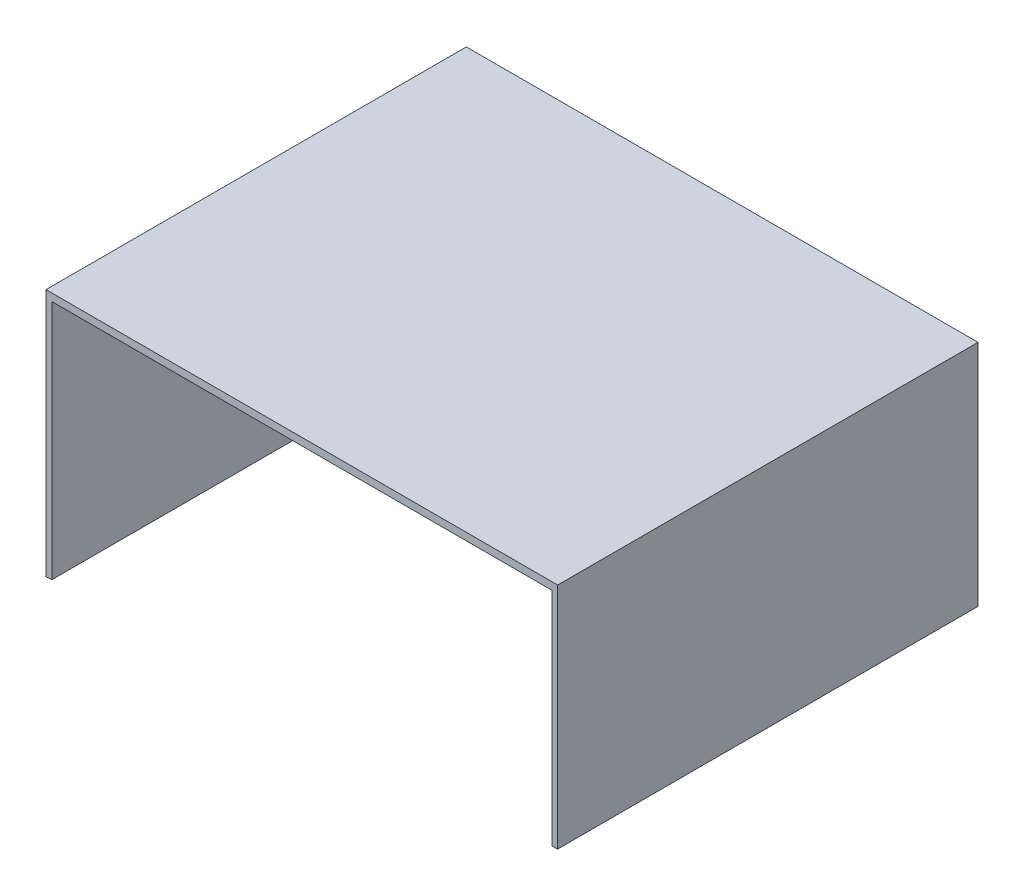
SolidWorks part; units mm, degrees
ref_plane "Front Plane" through (0, 0, 0) normal (0, 0, 1) x (1, 0, 0)
ref_plane "Top Plane" through (0, 0, 0) normal (0, 1, 0) x (1, 0, 0)
ref_plane "Right Plane" through (0, 0, 0) normal (1, 0, 0) x (0, 0, -1)
sketch "Sketch1" plane through (0, 0, 0) normal (0, 0, 1) x (1, 0, 0)
  line L0 (-65.8607, -67.9379) -> (-65.8607, 60.3528)
  line L1 (-65.8607, 60.3528) -> (198.1736, 60.3528)
  line L2 (198.1736, 60.3528) -> (198.1736, -57.6543)
  line L3 (198.1736, -57.6543) -> (195.1922, -57.7704)
  line L4 (195.1922, -57.7704) -> (195.1922, 56.5216)
  line L5 (195.1922, 56.5216) -> (-62.8793, 56.5216)
  line L6 (-62.8793, 56.5216) -> (-62.8793, -67.8218)
  line L7 (-62.8793, -67.8218) -> (-65.8607, -67.9379)
  point P2 (108.1901, -66.9817)
  point P9 (105.1856, -66.9025)
  point P10 (198.1736, -57.6543)
extrude "Boss-Extrude1" add sketch "Sketch1" along normal blind 216.916
